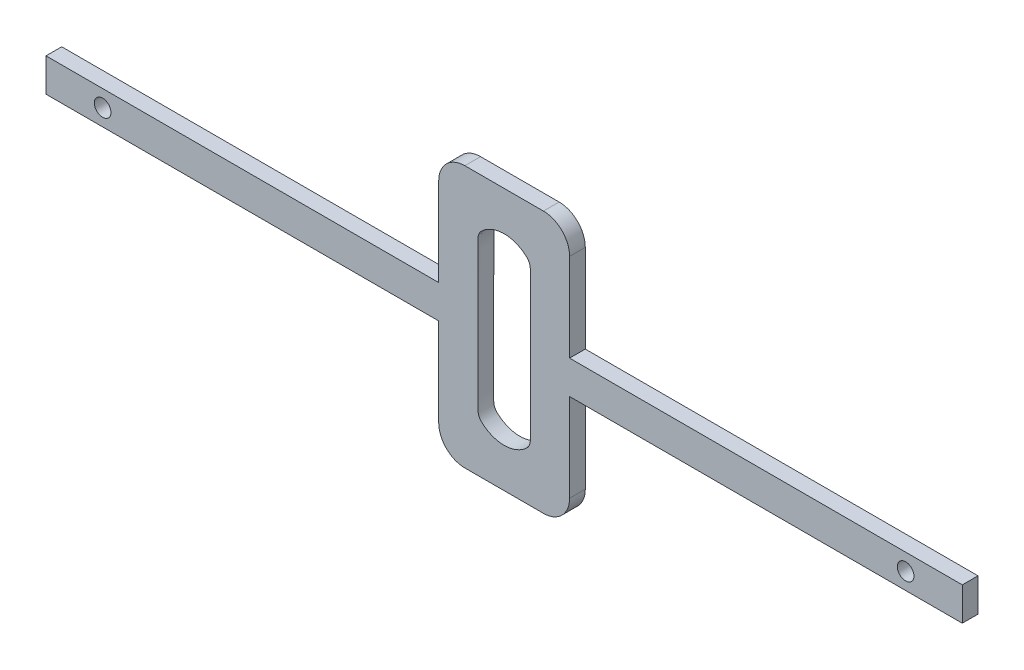
SolidWorks part; units mm, degrees
ref_plane "Alzado" through (0, 0, 0) normal (0, 0, 1) x (1, 0, 0)
ref_plane "Planta" through (0, 0, 0) normal (0, 1, 0) x (1, 0, 0)
ref_plane "Vista lateral" through (0, 0, 0) normal (1, 0, 0) x (0, 0, -1)
sketch "Croquis1" plane through (0, 0, 0) normal (0, 0, 1) x (1, 0, 0)
  line L0 (0, 35) -> (0, -35) construction
  line L1 (15, -50) -> (-15, -50)
  line L2 (25, -40) -> (25, 40)
  line L3 (15, 50) -> (-15, 50)
  line L4 (-25, -40) -> (-25, 40)
  line L5 (25, -50) -> (-25, 50) construction
  line L6 (25, 50) -> (-25, -50) construction
  line L7 (-10, -30) -> (-10, 30) construction
  line L9 (10, -30) -> (10, 30) construction
  line L10 (25, -50) -> (25, 50) construction
  line L11 (25, 50) -> (-25, 50) construction
  line L12 (25, -50) -> (-25, -50) construction
  line L13 (-25, -50) -> (-25, 50) construction
  line L14 (0, 35) -> (0, 15) construction
  line L15 (10, 35) -> (-10, 35) construction
  line L16 (-10, -35) -> (-10, 35) construction
  line L17 (10, -35) -> (10, 35) construction
  line L18 (-20.764, 0) -> (16.6525, 0) construction
  line L19 (10, -35) -> (-10, -35) construction
  arc A0 (25, 40) -> (15, 50) centre (15, 40) ccw
  arc A1 (15, -50) -> (25, -40) centre (15, -40) ccw
  arc A2 (-15, -50) -> (-25, -40) centre (-15, -40) cw
  arc A3 (-15, 50) -> (-25, 40) centre (-15, 40) ccw
  arc A4 (-10, -30) -> (10, -30) centre (0, -22.5) ccw construction
  arc A5 (-10, 30) -> (10, 30) centre (0, 22.5) cw construction
  spline S0 degree 3 poles (-10, -24.2562) (-10, -8.0854) (-10, 8.0854) (-10, 24.2562) (-10, 24.6547) (-10, 25.4517) (-10, 26.6472) (-10, 27.4442) (-10, 27.8427) (-10, 28.3646) (-10, 29.4083) (-9.2114, 31.0937) (-8.41, 31.7625) (-8.0093, 32.0969) (-7.7627, 32.3027) (-7.2694, 32.7144) (-6.4411, 33.2272) (-5.8775, 33.5367) (-5.5902, 33.6803) (-2.0045, 35.4732) (2.0045, 35.4732) (5.5902, 33.6803) (5.8775, 33.5367) (6.4411, 33.2272) (7.2694, 32.7144) (7.7627, 32.3027) (8.0093, 32.0969) (8.41, 31.7625) (9.2114, 31.0937) (10, 29.4083) (10, 28.3646) (10, 27.8427) (10, 27.4442) (10, 26.6472) (10, 25.4517) (10, 24.6547) (10, 24.2562) (10, 8.0854) (10, -8.0854) (10, -24.2562) (10, -24.6547) (10, -25.4517) (10, -26.6472) (10, -27.4442) (10, -27.8427) (10, -28.3646) (10, -29.4083) (9.2114, -31.0937) (8.41, -31.7625) (8.0093, -32.0969) (7.7627, -32.3027) (7.2694, -32.7144) (6.4411, -33.2272) (5.8775, -33.5367) (5.5902, -33.6803) (2.0045, -35.4732) (-2.0045, -35.4732) (-5.5902, -33.6803) (-5.8775, -33.5367) (-6.4411, -33.2272) (-7.2694, -32.7144) (-7.7627, -32.3027) (-8.0093, -32.0969) (-8.41, -31.7625) (-9.2114, -31.0937) (-10, -29.4083) (-10, -28.3646) (-10, -27.8427) (-10, -27.4442) (-10, -26.6472) (-10, -25.4517) (-10, -24.6547) (-10, -24.2562) (-10, -8.0854) (-10, 8.0854) knots -0.007286 0 0 0 0.295655 0.295655 0.295655 0.302941 0.310227 0.317513 0.317513 0.317513 0.327054 0.336596 0.346138 0.346138 0.346138 0.352011 0.357885 0.363759 0.363759 0.363759 0.431896 0.431896 0.431896 0.43777 0.443644 0.449517 0.449517 0.449517 0.459059 0.468601 0.478142 0.478142 0.478142 0.485428 0.492714 0.5 0.5 0.5 0.795655 0.795655 0.795655 0.802941 0.810227 0.817513 0.817513 0.817513 0.827054 0.836596 0.846138 0.846138 0.846138 0.852011 0.857885 0.863759 0.863759 0.863759 0.931896 0.931896 0.931896 0.93777 0.943644 0.949517 0.949517 0.949517 0.959059 0.968601 0.978142 0.978142 0.978142 0.985428 0.992714 1 1 1 1.295655 1.295655 1.295655 weights 1 1 1 1 1 1 1 1 1 1 1 1 1 1 1 1 1 1 1 0.929618 0.929618 1 1 1 1 1 1 1 1 1 1 1 1 1 1 1 1 1 1 1 1 1 1 1 1 1 1 1 1 1 1 1 1 1 1 0.929618 0.929618 1 1 1 1 1 1 1 1 1 1 1 1 1 1 1 1 1 1 only from (-10, -24.2562) to (-10, -24.2562)
  point P0 (0, 0)
  dimension "D4" = 10
  dimension "D1" = 100
  dimension "D2" = 50
  dimension "D5" = 20
  dimension "D3" = 15
extrude "Saliente-Extruir1" add sketch "Croquis1" along normal blind 6
sketch "Croquis2" plane through (25, 0, 0) normal (1, 0, 0) x (0, 0, -1)
  line L0 (0, 0) -> (-6, 0) construction
  line L1 (0, -40) -> (0, 40) construction
  line L2 (-6, -40) -> (-6, 40) construction
  line L4 (-6, -6.35) -> (0, -6.35)
  line L5 (-6, -6.35) -> (-6, 6.35)
  line L6 (-6, 6.35) -> (0, 6.35)
  line L7 (0, -6.35) -> (0, 6.35)
  line L8 (-6, -6.35) -> (0, 6.35) construction
  line L9 (-6, 6.35) -> (0, -6.35) construction
  point P6 (-3, 0)
  dimension "D1" = 12.7
extrude "Saliente-Extruir2" add sketch "Croquis2" along normal blind 150
mirror "Simetría1" about plane through (0, 0, 0) normal (1, 0, 0) of "Saliente-Extruir2", "Saliente-Extruir1"
sketch "Croquis3" plane through (0, 0, 6) normal (0, 0, 1) x (1, 0, 0)
  line L0 (0, 80.1519) -> (0, -66.7639) construction
  circle A0 centre (-153.3593, 0) radius 3.175
  circle A1 centre (153.3593, 0) radius 3.175
  dimension "D1" = 6.35
extrude "Cortar-Extruir1" cut sketch "Croquis3" against normal through all
